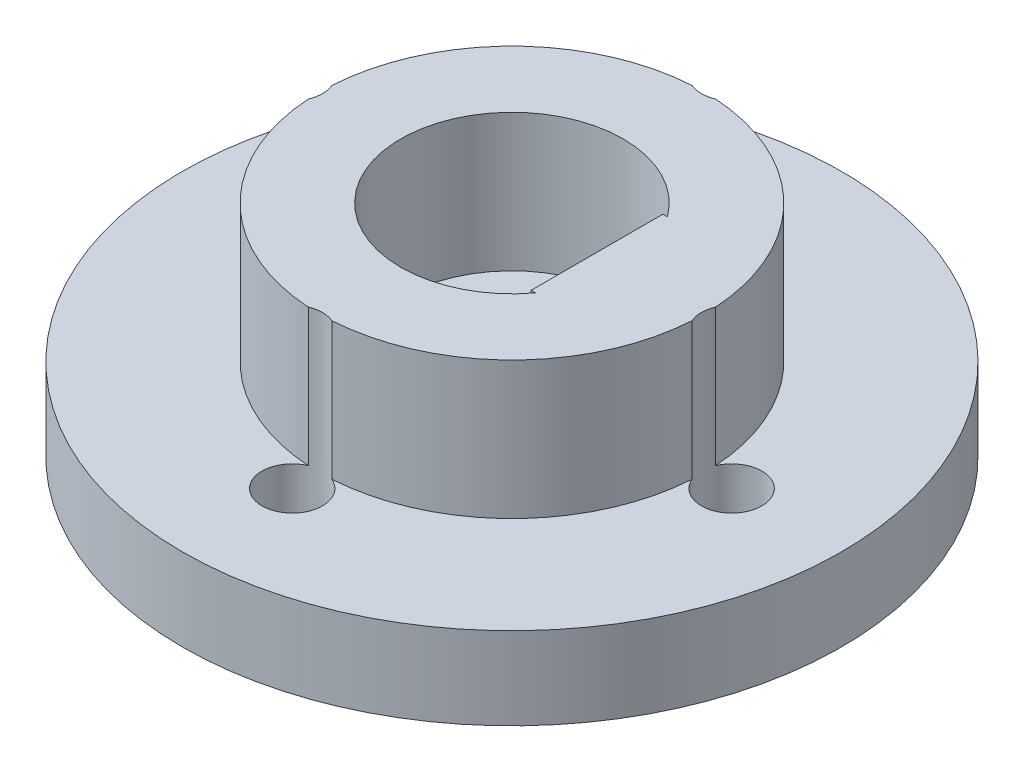
SolidWorks part; units mm, degrees
ref_plane "Front Plane" through (0, 0, 0) normal (0, 0, 1) x (1, 0, 0)
ref_plane "Top Plane" through (0, 0, 0) normal (0, 1, 0) x (1, 0, 0)
ref_plane "Right Plane" through (0, 0, 0) normal (1, 0, 0) x (0, 0, -1)
sketch "Stock_horn_drive_flange_profile" plane through (0, 0, 0) normal (0, 1, 0) x (1, 0, 0)
  circle A0 centre (0, 0) radius 12
  circle A1 centre (0, 0) radius 1.75
  dimension "D1" = 24
  dimension "D2" = 3.5
extrude "Stock_horn_drive_flange" add sketch "Stock_horn_drive_flange_profile" along normal blind 3 from offset 40
sketch "D_coupling_ring_profile" plane through (0, 0, 0) normal (0, 1, 0) x (1, 0, 0)
  circle A0 centre (0, 0) radius 7
  circle A1 centre (0, 0) radius 4.05
  dimension "D1" = 14
  dimension "D2" = 8.1
extrude "D_coupling_ring" add sketch "D_coupling_ring_profile" along normal blind 5 from offset 43
sketch "D_key_land_profile" plane through (0, 0, 0) normal (0, 1, 0) x (1, 0, 0)
  line L1 (3.1, -2.4) -> (6, -2.4)
  line L2 (3.1, -2.4) -> (3.1, 2.4)
  line L3 (3.1, 2.4) -> (6, 2.4)
  line L4 (6, -2.4) -> (6, 2.4)
  dimension "D1" = 2.9
  dimension "D2" = 4.8
extrude "D_key_land" add sketch "D_key_land_profile" along normal blind 5 from offset 43
sketch "Stock_horn_screws_profile" plane through (0, 0, 0) normal (0, 1, 0) x (1, 0, 0)
  circle A0 centre (-8, 0) radius 1.1
  circle A1 centre (8, 0) radius 1.1
  circle A2 centre (0, -8) radius 1.1
  circle A3 centre (0, 8) radius 1.1
  dimension "D1" = 2.2
  dimension "D2" = 2.2
  dimension "D3" = 2.2
  dimension "D4" = 2.2
extrude "Stock_horn_screws" cut sketch "Stock_horn_screws_profile" along normal through all from offset 39
